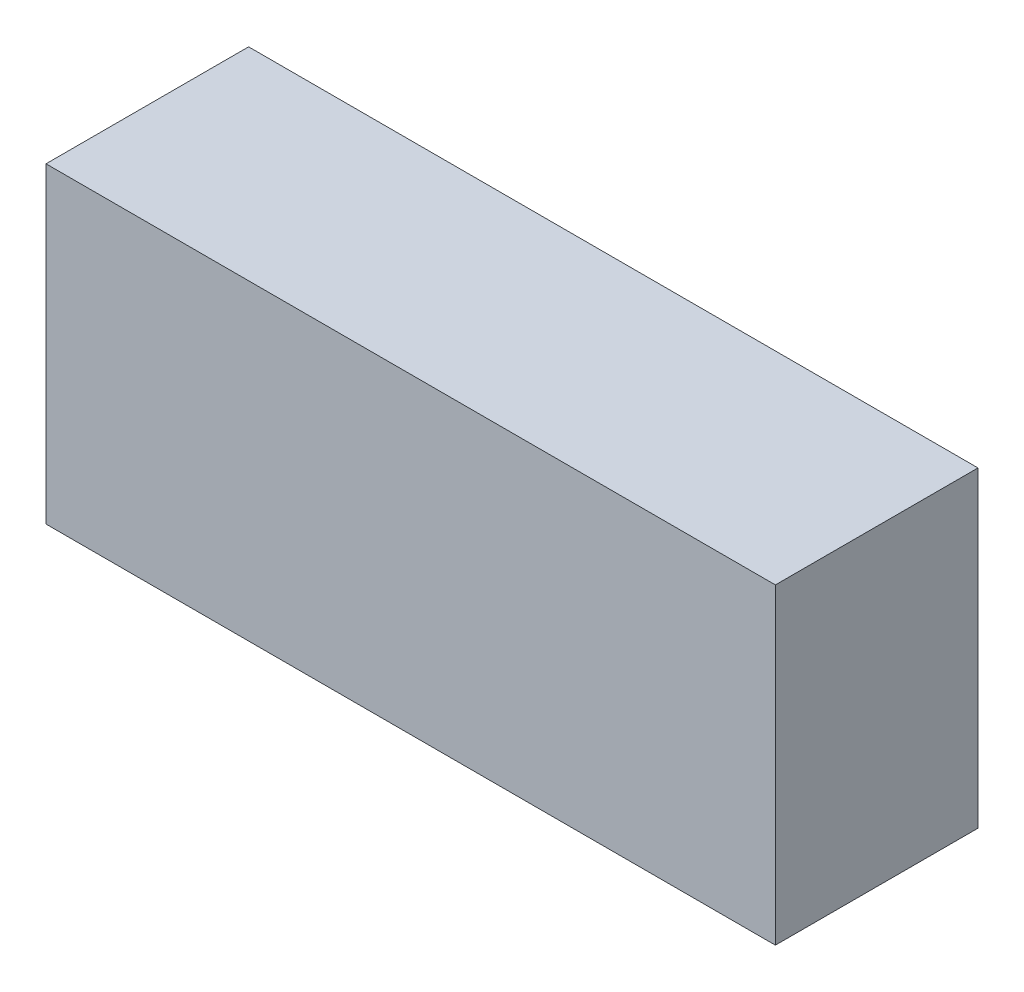
SolidWorks part; units mm, degrees
ref_plane "前视基准面" through (0, 0, 0) normal (0, 0, 1) x (1, 0, 0)
ref_plane "上视基准面" through (0, 0, 0) normal (0, 1, 0) x (1, 0, 0)
ref_plane "右视基准面" through (0, 0, 0) normal (1, 0, 0) x (0, 0, -1)
other "Configuration Table"
sketch "草图1" plane through (0, 0, 0) normal (0, 1, 0) x (1, 0, 0)
  line L1 (-45, 12.5) -> (45, 12.5)
  line L2 (-45, 12.5) -> (-45, -12.5)
  line L3 (-45, -12.5) -> (45, -12.5)
  line L4 (45, 12.5) -> (45, -12.5)
  line L5 (-45, 12.5) -> (45, -12.5) construction
  line L6 (-45, -12.5) -> (45, 12.5) construction
  point P0 (0, 0)
  dimension "D1" = 90
  dimension "D2" = 25
extrude "凸台-拉伸1" add sketch "草图1" along normal blind 38.5
